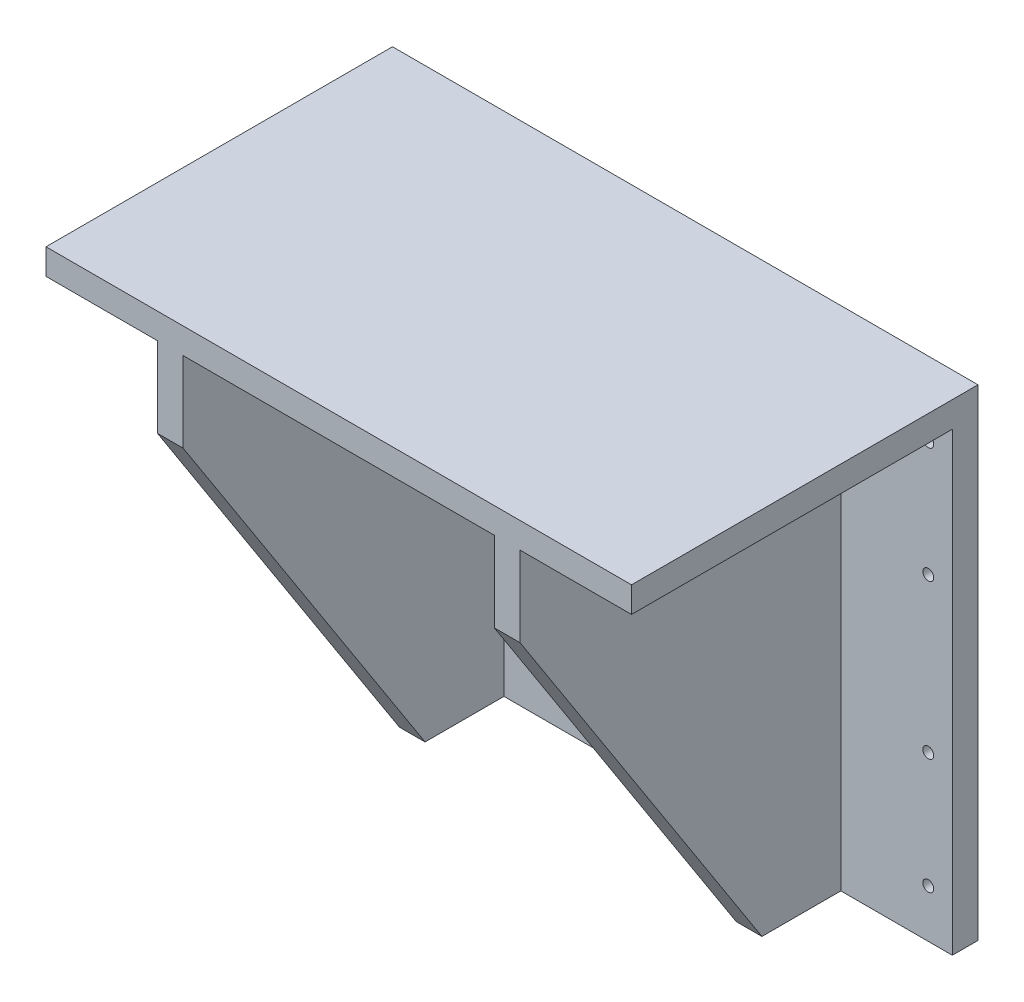
SolidWorks part; units mm, degrees
ref_plane "Front" through (0, 0, 0) normal (0, 0, 1) x (1, 0, 0)
ref_plane "Top" through (0, 0, 0) normal (0, 1, 0) x (1, 0, 0)
ref_plane "Right" through (0, 0, 0) normal (1, 0, 0) x (0, 0, -1)
sketch "Sketch1" plane through (0, 0, 0) normal (0, 0, 1) x (1, 0, 0)
  line L0 (0, 29.2187) -> (0, -353.7568) construction
  line L1 (-182.5, 0) -> (182.5, 0)
  line L2 (-182.5, 0) -> (-182.5, -300)
  line L3 (-182.5, -300) -> (182.5, -300)
  line L4 (182.5, 0) -> (182.5, -300)
  dimension "D1" = 365
  dimension "D2" = 300
extrude "Boss-Extrude1" add sketch "Sketch1" along normal blind 16
sketch "Sketch2" plane through (0, 0, 16) normal (0, 0, 1) x (1, 0, 0)
  line L0 (182.5, -300) -> (182.5, 0) construction
  line L1 (-182.5, 0) -> (182.5, 0)
  line L2 (-182.5, 0) -> (-182.5, -16)
  line L3 (-182.5, -16) -> (182.5, -16)
  line L4 (182.5, 0) -> (182.5, -16)
  dimension "D1" = 16
extrude "Boss-Extrude2" add sketch "Sketch2" along normal blind 200
sketch "Sketch3" plane through (182.5, 0, 0) normal (1, 0, 0) x (0, 0, -1)
  line L0 (-216, -16) -> (-216, -66)
  line L1 (-216, -16) -> (-16, -16) construction
  line L2 (-216, -66) -> (-65.1973, -300)
  line L3 (-65.1973, -300) -> (-16, -300)
  line L4 (-16, -300) -> (-16, -16) construction
  line L5 (-16, -300) -> (-16, -16)
  line L6 (-16, -16) -> (-216, -16)
  line L7 (-16, -300) -> (0, -300) construction
  line L8 (-216, -16) -> (-216, 0) construction
  dimension "D1" = 50
  dimension "D2" = 147.2
extrude "Boss-Extrude3" add sketch "Sketch3" against normal blind 16 from offset 69.5 offset against normal yes
sketch "Sketch4" plane through (97, 0, 0) normal (-1, 0, 0) x (0, 0, 1)
  line L5 (216, -16) -> (16, -16)
  line L6 (16, -16) -> (16, -300)
  line L7 (16, -300) -> (65.1973, -300)
  line L8 (65.1973, -300) -> (216, -66)
  line L9 (216, -66) -> (216, -16)
  line L10 (216, -16) -> (16, -16)
  line L11 (16, -16) -> (16, -300)
  line L12 (16, -300) -> (65.1973, -300)
  line L13 (65.1973, -300) -> (216, -66)
  line L14 (216, -66) -> (216, -16)
  dimension "D1" = 0
extrude "Boss-Extrude4" add sketch "Sketch4" along normal blind 16 from offset 194
hole_wizard "M8x1.25 Tapped Hole1" positions "Sketch6" profile "Sketch5" tap size "M8x1.25" standard "JIS" end condition through all
sketch "Sketch6" plane through (0, 0, 16) normal (0, 0, 1) x (1, 0, 0)
  line L0 (0, -320.3046) -> (0, 28.3357) construction
  line L2 (182.5, -300) -> (182.5, -16) construction
  line L3 (182.5, 0) -> (-182.5, 0) construction
  point P0 (167.5, -30)
  point P11 (167.5, -270)
  point P14 (167.5, -198)
  point P16 (167.5, -102)
  dimension "D1" = 15
  dimension "D2" = 96
  dimension "D3" = 72
  dimension "D4" = 30
  dimension "D5" = 72
sketch "Sketch5" plane through (167.5, -30, 16) normal (1, 0, 0) x (0, -1, 0)
  line L0 (0, 0) -> (0, 16)
  line L1 (0, 16) -> (3.4, 16)
  line L2 (3.4, 16) -> (3.4, 0)
  line L5 (3.4, 0) -> (0, 0)
  line L11 (0, -6.35) -> (0, 107.95) construction
  dimension "Thru Tap Drill Dia." = 6.8
  dimension "Thru Tap Drill Depth" = 16
cosmetic thread "Hole Thread1" parameters "D2"=8
cosmetic thread "Hole Thread2" parameters "D2"=8
cosmetic thread "Hole Thread3" parameters "D2"=8
cosmetic thread "Hole Thread4" parameters "D2"=8
pattern_linear "LPattern1" count 2 spacing 335 along (-1, 0, 0) of "M8x1.25 Tapped Hole1"
